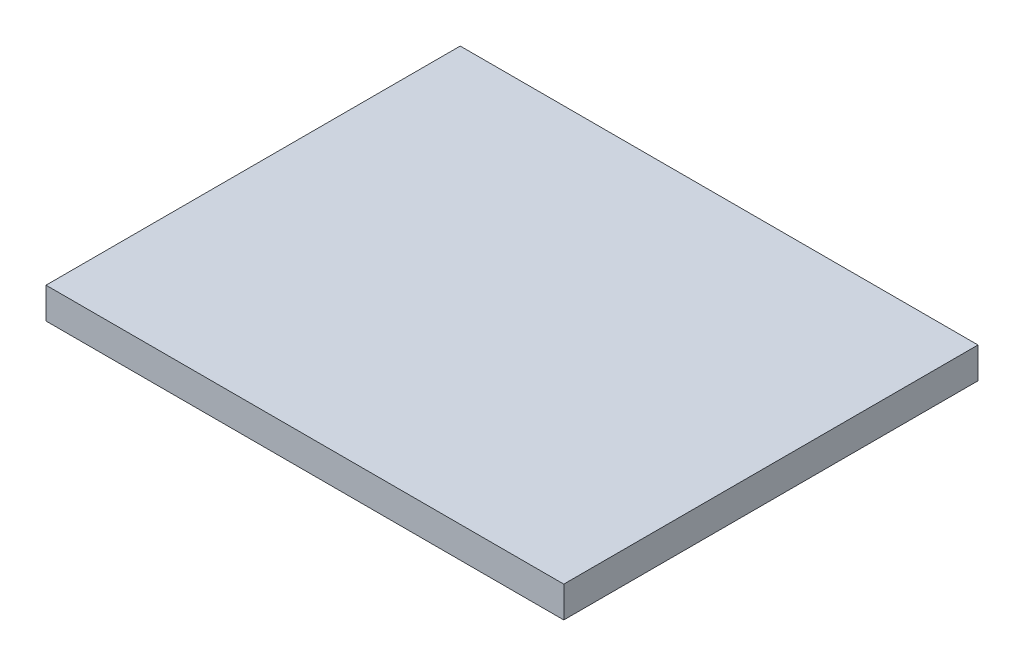
SolidWorks part; units mm, degrees
ref_plane "前视基准面" through (0, 0, 0) normal (0, 0, 1) x (1, 0, 0)
ref_plane "上视基准面" through (0, 0, 0) normal (0, 1, 0) x (1, 0, 0)
ref_plane "右视基准面" through (0, 0, 0) normal (1, 0, 0) x (0, 0, -1)
other "Configuration Table"
sketch "草图1" plane through (0, 0, 0) normal (0, 1, 0) x (1, 0, 0)
  line L1 (0, 0) -> (50, 0)
  line L2 (0, 0) -> (0, 40)
  line L3 (0, 40) -> (50, 40)
  line L4 (50, 0) -> (50, 40)
  dimension "D1" = 40
  dimension "D2" = 50
extrude "凸台-拉伸1" add sketch "草图1" along normal blind 3
